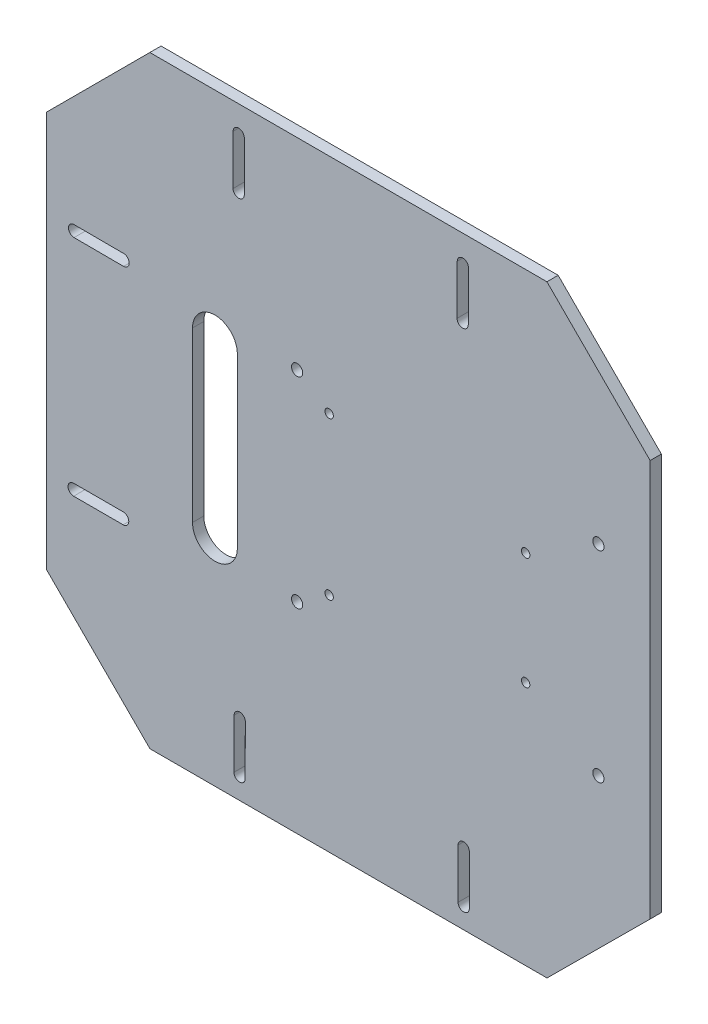
SolidWorks part; units mm, degrees
ref_plane "Front Plane" through (0, 0, 0) normal (0, 0, 1) x (1, 0, 0)
ref_plane "Top Plane" through (0, 0, 0) normal (0, 1, 0) x (1, 0, 0)
ref_plane "Right Plane" through (0, 0, 0) normal (1, 0, 0) x (0, 0, -1)
sketch "Sketch1" plane through (0, 0, 0) normal (0, 0, 1) x (1, 0, 0)
  line L0 (-73.5976, 117.2814) -> (67.8633, 117.2814)
  line L1 (-110.3672, 80.5118) -> (-110.3672, -60.7021)
  line L2 (-73.5668, -97.5025) -> (67.8941, -97.5025)
  line L3 (104.6328, 80.5118) -> (104.6328, -60.9491)
  line L6 (104.6328, 80.5118) -> (67.8633, 117.2814)
  line L7 (67.8941, -97.5025) -> (104.6328, -60.9491)
  line L8 (-110.3672, -60.7021) -> (-73.5668, -97.5025)
  line L9 (-73.5976, 117.2814) -> (-110.3672, 80.5118)
  line L10 (-106.1246, 84.7545) -> (-77.8403, 113.0387)
  line L23 (-92.7181, 99.6354) -> (-92.6579, 99.6956)
  line L26 (-110.3672, 29.5608) -> (-110.3672, -10.4392)
  line L32 (-110.3672, -10.4392) -> (-110.3672, -5.1592) construction
  line L34 (-110.3672, 80.5118) -> (-110.3672, 9.9049) construction
  line L57 (-50.4034, -20.0951) -> (-50.4034, 39.9049) construction
  line L58 (-67.9409, 117.2814) -> (-3.0009, 117.2814) construction
  line L60 (-67.9409, 117.2814) -> (-50.4034, 117.2814) construction
  line L63 (-110.3672, 39.9049) -> (-110.3672, -20.0951)
  line L64 (-58.3858, -20.0951) -> (-58.3858, 39.9049)
  line L65 (-42.4209, -20.0951) -> (-42.4209, 39.9049)
  line L66 (-41.9513, 90.1358) -> (-41.9513, 107.7809) construction
  line L67 (-43.9513, 90.1358) -> (-43.9513, 107.7809)
  line L68 (-39.9513, 90.1358) -> (-39.9513, 107.7809)
  line L71 (-33.0009, 117.2814) -> (26.9991, 117.2814)
  line L73 (-83.0981, -31.1792) -> (-100.7432, -31.1792) construction
  line L74 (37.8396, 89.9786) -> (37.9109, 107.6236) construction
  line L75 (39.8396, 89.9706) -> (39.9109, 107.6155)
  line L76 (-73.5976, 117.2814) -> (-110.3672, 80.5118)
  line L85 (35.8396, 89.9867) -> (35.9109, 107.6317)
  line L86 (-83.0981, -33.1792) -> (-100.7432, -33.1792)
  line L88 (-83.0981, -29.1792) -> (-100.7432, -29.1792)
  line L90 (-82.941, 48.6116) -> (-100.5859, 48.6829) construction
  line L91 (-82.9329, 50.6116) -> (-100.5779, 50.6829)
  line L92 (-82.9491, 46.6117) -> (-100.594, 46.683)
  line L93 (38.2169, -72.3261) -> (38.2169, -89.9712) construction
  line L94 (40.2169, -72.3261) -> (40.2169, -89.9712)
  line L95 (36.2169, -72.3261) -> (36.2169, -89.9712)
  line L96 (-41.574, -72.1689) -> (-41.6453, -89.8139) construction
  line L97 (-43.574, -72.1608) -> (-43.6453, -89.8058)
  line L98 (-39.574, -72.177) -> (-39.6453, -89.822)
  line L106 (32.5322, 66.3803) -> (32.5322, -53.3476) construction
  line L107 (-27.4678, 49.8259) -> (92.5322, 49.8259)
  line L108 (-27.4678, 49.8259) -> (-27.4678, -30.1741)
  line L109 (-27.4678, -30.1741) -> (92.5322, -30.1741)
  line L110 (92.5322, 49.8259) -> (92.5322, -30.1741)
  line L111 (-27.4678, 49.8259) -> (92.5322, -30.1741) construction
  line L112 (-27.4678, -30.1741) -> (92.5322, 49.8259) construction
  line L142 (79.2066, -30.8019) -> (96.8515, -30.8732) construction
  line L143 (79.2147, -28.8019) -> (96.8596, -28.8732)
  line L144 (79.1985, -32.8019) -> (96.8435, -32.8732)
  line L145 (79.3637, 48.989) -> (97.0088, 48.989) construction
  line L146 (79.3637, 50.989) -> (97.0088, 50.989)
  line L147 (79.3637, 46.989) -> (97.0088, 46.989)
  line L148 (79.2066, -30.8019) -> (96.8515, -30.8732) construction
  line L149 (79.2147, -28.8019) -> (96.8596, -28.8732)
  line L150 (79.1985, -32.8019) -> (96.8435, -32.8732)
  line L151 (79.3637, 48.989) -> (97.0088, 48.989) construction
  line L152 (79.3637, 50.989) -> (97.0088, 50.989)
  line L153 (79.3637, 46.989) -> (97.0088, 46.989)
  arc A33 (-58.3858, -20.0951) -> (-42.4209, -20.0951) centre (-50.4034, -20.0951) ccw
  arc A34 (-42.4209, 39.9049) -> (-58.3858, 39.9049) centre (-50.4034, 39.9049) ccw
  arc A35 (-43.9513, 90.1358) -> (-39.9513, 90.1358) centre (-41.9513, 90.1358) ccw
  arc A36 (-39.9513, 107.7809) -> (-43.9513, 107.7809) centre (-41.9513, 107.7809) ccw
  arc A37 (39.8396, 89.9706) -> (35.8396, 89.9867) centre (37.8396, 89.9786) cw
  arc A38 (35.9109, 107.6317) -> (39.9109, 107.6155) centre (37.9109, 107.6236) cw
  arc A39 (-83.0981, -33.1792) -> (-83.0981, -29.1792) centre (-83.0981, -31.1792) ccw
  arc A40 (-100.7432, -29.1792) -> (-100.7432, -33.1792) centre (-100.7432, -31.1792) ccw
  arc A41 (-82.9329, 50.6116) -> (-82.9491, 46.6117) centre (-82.941, 48.6116) cw
  arc A42 (-100.594, 46.683) -> (-100.5779, 50.6829) centre (-100.5859, 48.6829) cw
  arc A43 (40.2169, -72.3261) -> (36.2169, -72.3261) centre (38.2169, -72.3261) ccw
  arc A44 (36.2169, -89.9712) -> (40.2169, -89.9712) centre (38.2169, -89.9712) ccw
  arc A45 (-43.574, -72.1608) -> (-39.574, -72.177) centre (-41.574, -72.1689) cw
  arc A46 (-39.6453, -89.822) -> (-43.6453, -89.8058) centre (-41.6453, -89.8139) cw
  circle A51 centre (-9.7178, 37.8259) radius 1.5
  circle A52 centre (60.2822, 29.8259) radius 1.5
  circle A53 centre (60.2822, -10.1741) radius 1.5
  circle A54 centre (-9.7178, -18.1741) radius 1.5
  circle A55 centre (-21.1318, 45.6019) radius 2
  circle A56 centre (86.1963, 45.6019) radius 2
  circle A57 centre (86.1963, -25.9502) radius 2
  circle A58 centre (-21.1318, -25.9502) radius 2
  arc A83 (79.2147, -28.8019) -> (79.1985, -32.8019) centre (79.2066, -30.8019) ccw
  arc A84 (96.8435, -32.8732) -> (96.8596, -28.8732) centre (96.8515, -30.8732) ccw
  arc A85 (79.3637, 50.989) -> (79.3637, 46.989) centre (79.3637, 48.989) ccw
  arc A86 (97.0088, 46.989) -> (97.0088, 50.989) centre (97.0088, 48.989) ccw
  point P0 (-2.8672, 9.9049)
  point P8 (-91.9824, 99.0201)
  point P17 (-2.8672, 9.9049)
  point P18 (-91.9824, 98.8966)
  point P32 (0, 0)
  point P33 (-2.8672, 9.9049)
  point P38 (-120.1149, 127.1526)
  point P41 (-120.9422, 9.9076)
  point P85 (-50.4034, 9.9049)
  point P95 (-3.0168, 9.9309)
  point P97 (-41.9513, 98.9583)
  point P140 (32.5322, 9.8259)
  point P142 (37.8752, 98.8011)
  point P145 (-2.8672, 9.9049)
  point P152 (-91.9207, -31.1792)
  point P159 (-91.7635, 48.6473)
  point P166 (38.2169, -81.1486)
  point P173 (-41.6096, -80.9914)
  point P180 (88.0291, -30.8376)
  point P192 (-1.8672, 8.9049)
  point P197 (32.5322, 9.8259)
  point P218 (88.1863, 48.989)
  point P225 (88.0291, -30.8376)
  point P232 (88.1863, 48.989)
  point P239 (88.0291, -30.8376)
  point P246 (88.1863, 48.989)
  point P253 (88.0291, -30.8376)
  point P260 (88.1863, 48.989)
  point P267 (88.0291, -30.8376)
  point P274 (88.1863, 48.989)
  point P281 (88.0291, -30.8376)
  point P288 (88.1863, 48.989)
  point P295 (88.0291, -30.8376)
  point P302 (88.1863, 48.989)
  dimension "D19" = 2
  dimension "D20" = 4
  dimension "D22" = 2
  dimension "D24" = 3
  dimension "D25" = 3
  dimension "D28" = 4
  dimension "D1" = 52
  dimension "D2" = 141.4609
  dimension "D3" = 215
  dimension "D4" = 40
  dimension "D15" = 5.28
  dimension "D18" = 17.5375
  dimension "D21" = 64.94
  dimension "D26" = 120
  dimension "D29" = 71.5521
  dimension "D30" = 107.3282
extrude "Boss-Extrude2" add sketch "Sketch1" along normal blind 4
